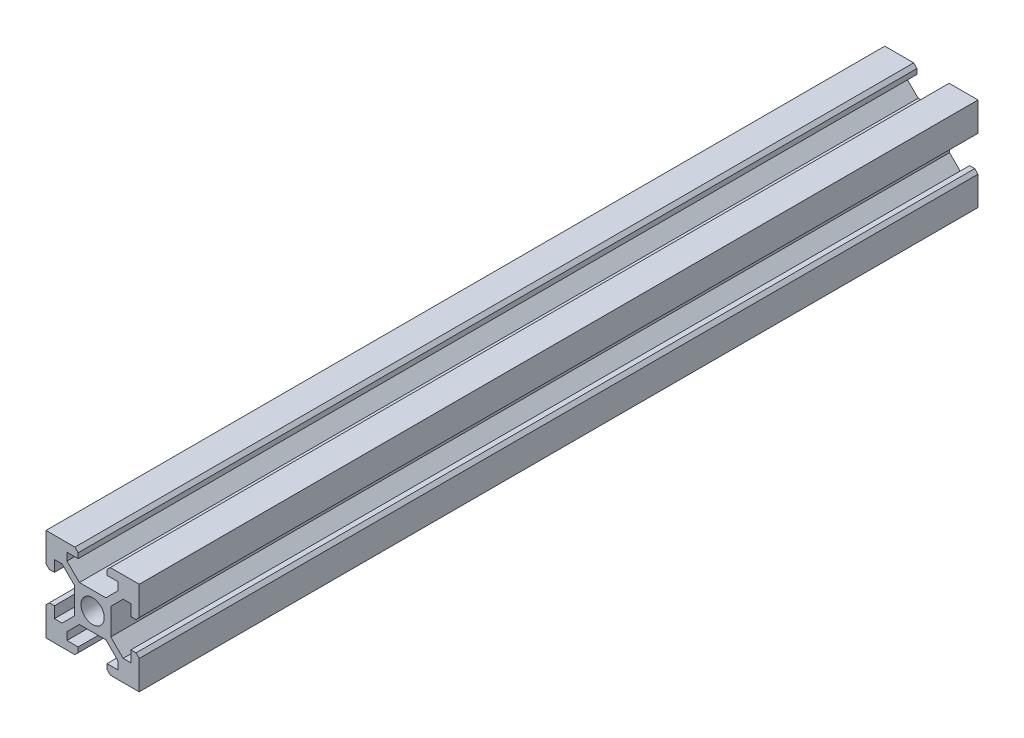
SolidWorks part; units mm, degrees
material "1060 Alloy"
ref_plane "Front Plane" through (0, 0, 0) normal (0, 0, 1) x (1, 0, 0)
ref_plane "Top Plane" through (0, 0, 0) normal (0, 1, 0) x (1, 0, 0)
ref_plane "Right Plane" through (0, 0, 0) normal (1, 0, 0) x (0, 0, -1)
sketch "Sketch1" plane through (0, 0, 0) normal (0, 0, 1) x (1, 0, 0)
  line L0 (3.9, -2.8393) -> (6.5607, -5.5)
  line L1 (-10, 10) -> (10, 10) construction
  line L2 (-10, 10) -> (-10, -10) construction
  line L3 (-10, -10) -> (10, -10) construction
  line L4 (10, 10) -> (10, -10) construction
  line L5 (-10, 10) -> (10, -10) construction
  line L6 (-10, -10) -> (10, 10) construction
  line L7 (-3.9, -3.9) -> (3.9, -3.9) construction
  line L8 (-3.9, -3.9) -> (-3.9, 3.9) construction
  line L9 (-3.9, 3.9) -> (3.9, 3.9) construction
  line L10 (3.9, -3.9) -> (3.9, 3.9) construction
  line L11 (-3.9, -3.9) -> (3.9, 3.9) construction
  line L12 (-3.9, 3.9) -> (3.9, -3.9) construction
  line L13 (-10, 10) -> (-5.5, 10) construction
  line L14 (-10, 10) -> (-10, 5.5) construction
  line L15 (-10, 5.5) -> (-5.5, 5.5) construction
  line L16 (-5.5, 10) -> (-5.5, 5.5) construction
  line L17 (10, 10) -> (5.5, 10) construction
  line L18 (10, 10) -> (10, 5.5) construction
  line L19 (10, 5.5) -> (5.5, 5.5) construction
  line L20 (5.5, 10) -> (5.5, 5.5) construction
  line L21 (-10, -10) -> (-5.5, -10) construction
  line L22 (-10, -10) -> (-10, -5.5) construction
  line L23 (-10, -5.5) -> (-5.5, -5.5) construction
  line L24 (-5.5, -10) -> (-5.5, -5.5) construction
  line L25 (10, -10) -> (5.5, -10) construction
  line L26 (10, -10) -> (10, -5.5) construction
  line L27 (10, -5.5) -> (5.5, -5.5) construction
  line L28 (5.5, -10) -> (5.5, -5.5) construction
  line L29 (2.8393, -3.9) -> (5.5, -6.5607)
  line L30 (-5.5, 6.5607) -> (-2.8393, 3.9)
  line L31 (-6.5607, 5.5) -> (-3.9, 2.8393)
  line L32 (5.5, 6.5607) -> (2.8393, 3.9)
  line L33 (6.5607, 5.5) -> (3.9, 2.8393)
  line L34 (-6.5607, -5.5) -> (-3.9, -2.8393)
  line L35 (-5.5, -6.5607) -> (-2.8393, -3.9)
  line L36 (-2.8393, 3.9) -> (2.8393, 3.9)
  line L37 (-3.9, 2.8393) -> (-3.9, -2.8393)
  line L38 (-2.8393, -3.9) -> (2.8393, -3.9)
  line L39 (3.9, -2.8393) -> (3.9, 2.8393)
  line L40 (5.5, 6.5607) -> (5.5, 8.2007)
  line L41 (5.5, 8.2007) -> (3.1, 8.2007)
  line L42 (3.1, 8.2007) -> (3.1, 9.3)
  line L43 (3.1, 9.3) -> (3.8, 10)
  line L44 (3.8, 10) -> (10, 10)
  line L45 (10, 10) -> (10, 3.8)
  line L46 (10, 3.8) -> (9.3, 3.1)
  line L47 (9.3, 3.1) -> (8.2007, 3.1)
  line L48 (8.2007, 3.1) -> (8.2007, 5.5)
  line L49 (8.2007, 5.5) -> (6.5607, 5.5)
  line L50 (3.1, -8.2007) -> (5.5, -8.2007)
  line L51 (3.1, -9.3) -> (3.1, -8.2007)
  line L52 (3.8, -10) -> (3.1, -9.3)
  line L53 (10, -10) -> (3.8, -10)
  line L54 (10, -3.8) -> (10, -10)
  line L55 (9.3, -3.1) -> (10, -3.8)
  line L56 (8.2007, -3.1) -> (9.3, -3.1)
  line L57 (8.2007, -5.5) -> (8.2007, -3.1)
  line L58 (6.5607, -5.5) -> (8.2007, -5.5)
  line L59 (5.5, -8.2007) -> (5.5, -6.5607)
  line L60 (-8.2007, -3.1) -> (-8.2007, -5.5)
  line L61 (-9.3, -3.1) -> (-8.2007, -3.1)
  line L62 (-10, -3.8) -> (-9.3, -3.1)
  line L63 (-10, -10) -> (-10, -3.8)
  line L64 (-3.8, -10) -> (-10, -10)
  line L65 (-3.1, -9.3) -> (-3.8, -10)
  line L66 (-3.1, -8.2007) -> (-3.1, -9.3)
  line L67 (-5.5, -8.2007) -> (-3.1, -8.2007)
  line L68 (-5.5, -6.5607) -> (-5.5, -8.2007)
  line L69 (-8.2007, -5.5) -> (-6.5607, -5.5)
  line L70 (-3.1, 8.2007) -> (-5.5, 8.2007)
  line L71 (-3.1, 9.3) -> (-3.1, 8.2007)
  line L72 (-3.8, 10) -> (-3.1, 9.3)
  line L73 (-10, 10) -> (-3.8, 10)
  line L74 (-10, 3.8) -> (-10, 10)
  line L75 (-9.3, 3.1) -> (-10, 3.8)
  line L76 (-8.2007, 3.1) -> (-9.3, 3.1)
  line L77 (-8.2007, 5.5) -> (-8.2007, 3.1)
  line L78 (-6.5607, 5.5) -> (-8.2007, 5.5)
  line L79 (-5.5, 8.2007) -> (-5.5, 6.5607)
  circle A0 centre (0, 0) radius 2.5
  point P83 (0, 0)
  dimension "D1" = 5
  dimension "D2" = 20
  dimension "D3" = 7.8
  dimension "D4" = 4.5
  dimension "D5" = 1.5
  dimension "D6" = 0.75
  dimension "D7" = 1.5
  dimension "D8" = 0.75
  dimension "D9" = 1.5
  dimension "D10" = 0.75
  dimension "D11" = 1.5
  dimension "D12" = 0.75
  dimension "D13" = 1.64
  dimension "D14" = 45
  dimension "D15" = 3.1
  dimension "D16" = 6.2
  dimension "D17" = 6.2
  dimension "D18" = 3.1
  dimension "D19" = 4
extrude "Boss-Extrude1" add sketch "Sketch1" along normal mid plane 180 contours L79 L70 L71 L72 L73 L74 L75 L76 L77 L78 L31 L37 L34 L69 L60 L61 L62 L63 L64 L65 L66 L67 L68 L35 L38 L29 L59 L50 L51 L52 L53 L54 L55 L56 L57 L58 L0 L39 L33 L49 L48 L47 L46 L45 L44 L43 L42 L41 L40 L32 L36
